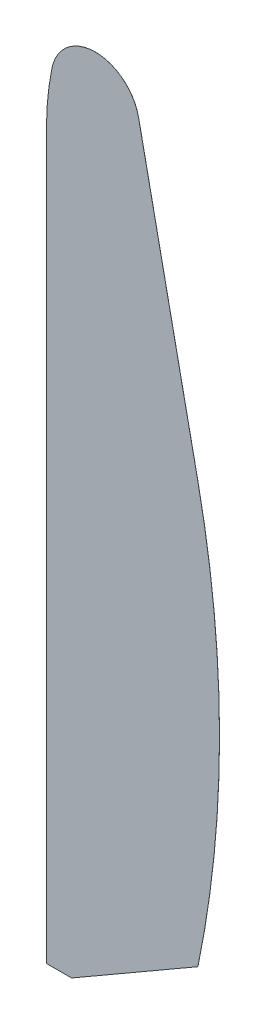
SolidWorks part; units mm, degrees
ref_plane "Front Plane" through (0, 0, 0) normal (1, 0, 0) x (0, 1, 0)
ref_plane "Top Plane" through (0, 0, 0) normal (0, 0, 1) x (0, 1, 0)
ref_plane "Right Plane" through (0, 0, 0) normal (0, 1, 0) x (-1, 0, 0)
sketch "Sketch1" plane through (0, 0, 0) normal (0, 0, 1) x (0, 1, 0)
  line L0 (0, 0) -> (0, 50000) construction
  line L1 (0, 0) -> (50000, 0) construction
  line L2 (143.5634, 601.065) -> (1381.2364, 932.6984) construction
  line L3 (0, 0) -> (144.15, 0)
  line L4 (0, 0) -> (0, -5)
  line L5 (0, -5) -> (14.5139, -30.1389)
  line L6 (155, -18.3382) -> (98.2385, -30.1389)
  line L7 (0, 0) -> (56.3762, -34.4444)
  line L8 (0, 0) -> (155, -18.3382)
  arc A0 (144.15, 0) -> (155, -1.1159) centre (144.15, -53.3044) cw
  arc A1 (155, -1.1159) -> (155, -18.3382) centre (153.2097, -9.727) cw
  arc A2 (14.5139, -30.1389) -> (98.2385, -30.1389) centre (56.3762, 171.2185) ccw
  dimension "D1" = 5
  dimension "D2" = 30.1389
  dimension "D3" = 144.15
  dimension "Span" = 155
  dimension "Chord" = 34.4444
  dimension "D4" = 30
  dimension "D5" = 17.2222
extrude "Boss-Extrude1" add sketch "Sketch1" along normal blind 0.01 contours L6 A2 L5 L4 L3 A0 A1
equation "\"D3@Sketch1\"=\"Span@Sketch1\"*0.93"
equation "\"D2@Sketch1\"=\"Chord@Sketch1\"*0.875"
equation "\"Chord@Sketch1\"=\"Span@Sketch1\"/4.5"
equation "\"D5@Sketch1\"=\"Chord@Sketch1\"/2"
